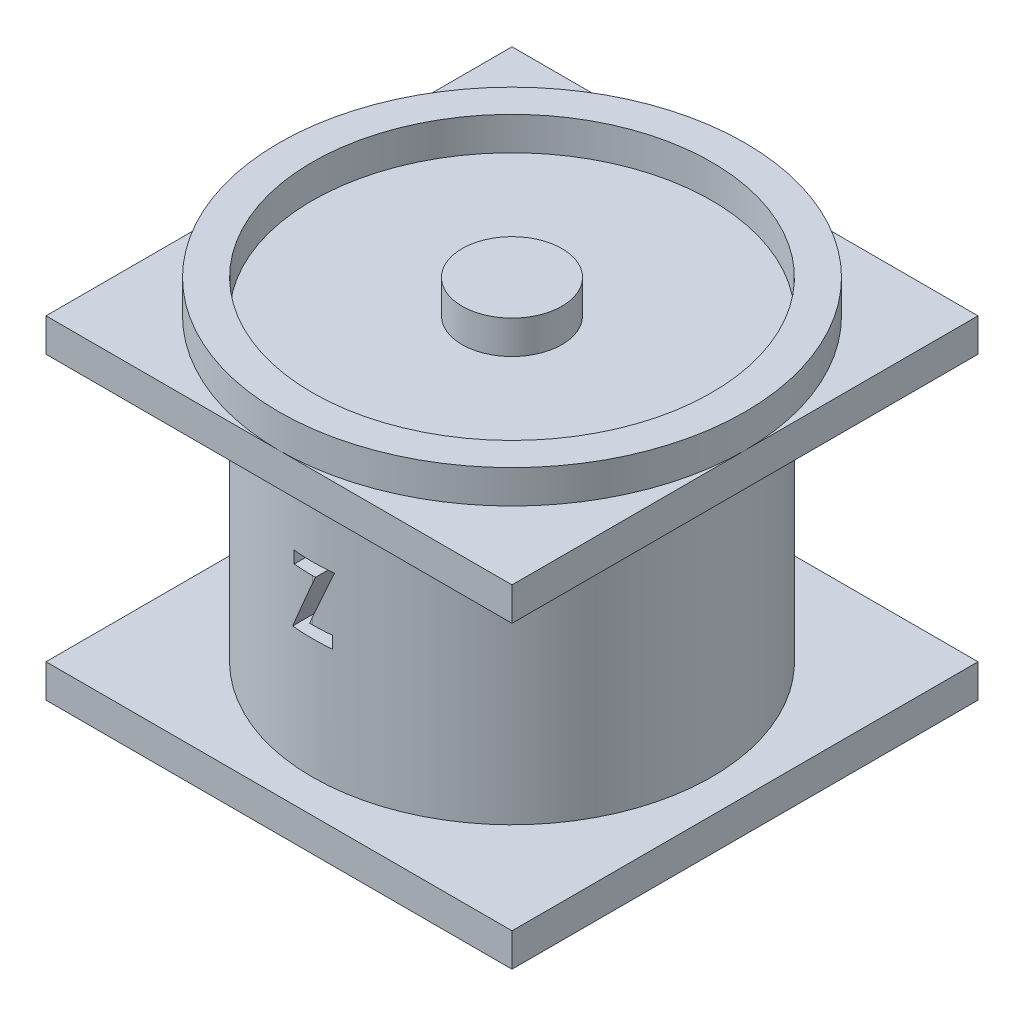
SolidWorks part; units mm, degrees
ref_plane "Front Plane" through (0, 0, 0) normal (0, 0, 1) x (1, 0, 0)
ref_plane "Top Plane" through (0, 0, 0) normal (0, 1, 0) x (1, 0, 0)
ref_plane "Right Plane" through (0, 0, 0) normal (1, 0, 0) x (0, 0, -1)
sketch "Sketch1" plane through (0, 0, 0) normal (0, 1, 0) x (1, 0, 0)
  line L1 (-70, 70) -> (70, 70)
  line L2 (-70, 70) -> (-70, -70)
  line L3 (-70, -70) -> (70, -70)
  line L4 (70, 70) -> (70, -70)
  line L5 (-70, 70) -> (70, -70) construction
  line L6 (-70, -70) -> (70, 70) construction
  point P0 (0, 0)
  dimension "D1" = 140
  dimension "D2" = 140
extrude "Boss-Extrude1" add sketch "Sketch1" along normal blind 10
sketch "Sketch2" plane through (0, 10, 0) normal (0, 1, 0) x (1, 0, 0)
  circle A0 centre (0, 0) radius 60
  dimension "D1" = 120
extrude "Boss-Extrude2" add sketch "Sketch2" along normal blind 80
sketch "Sketch3" plane through (0, 90, 0) normal (0, 1, 0) x (1, 0, 0)
  line L1 (-70, 70) -> (70, 70)
  line L2 (-70, 70) -> (-70, -70)
  line L3 (-70, -70) -> (70, -70)
  line L4 (70, 70) -> (70, -70)
  line L5 (-70, 70) -> (70, -70) construction
  line L6 (-70, -70) -> (70, 70) construction
  point P0 (0, 0)
extrude "Boss-Extrude3" add sketch "Sketch3" along normal blind 10
sketch "Sketch4" plane through (0, 100, 0) normal (0, 1, 0) x (1, 0, 0)
  circle A0 centre (0, 0) radius 70
  circle A1 centre (0, 0) radius 60
  dimension "D1" = 120
  dimension "D2" = 140
extrude "Boss-Extrude4" add sketch "Sketch4" along normal blind 10
sketch "Sketch5" plane through (0, 100, 0) normal (0, 1, 0) x (1, 0, 0)
  circle A0 centre (0, 0) radius 15
extrude "Boss-Extrude5" add sketch "Sketch5" along normal blind 10
ref_plane "Plane6" through (0, 0, 60) normal (0, 0, 1) x (1, 0, 0)
sketch "Sketch6" plane through (0, 0, 60) normal (0, 0, 1) x (1, 0, 0)
  text T0 "Z" font "Century Gothic" height 20
extrude "Cut-Extrude1" cut sketch "Sketch6" against normal blind 10
